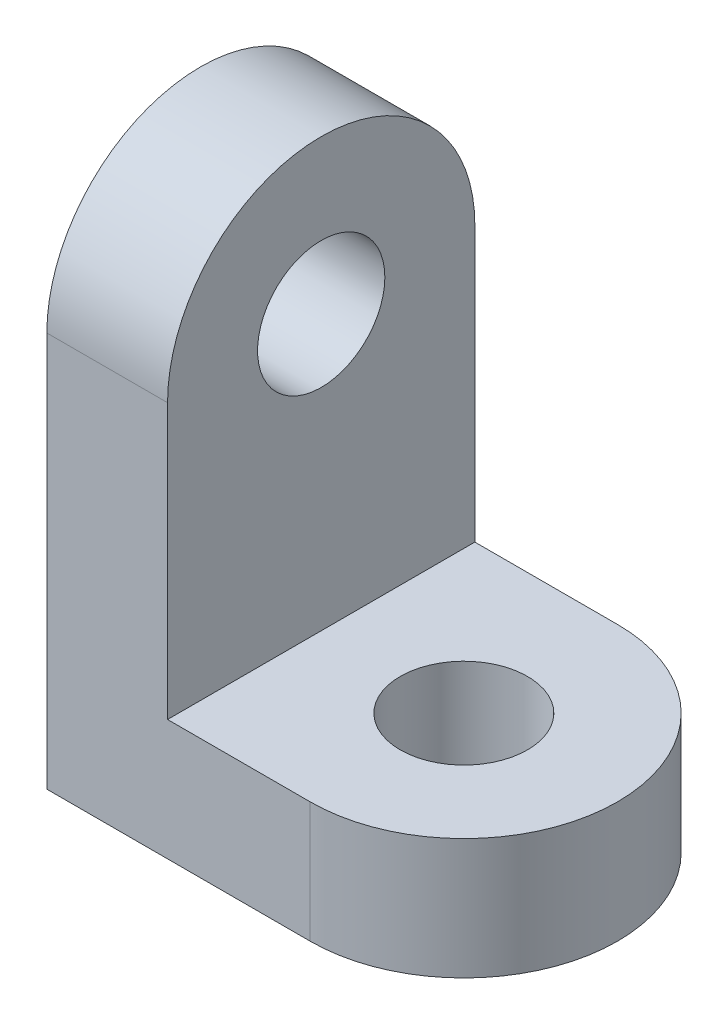
SolidWorks part; units mm, degrees
ref_plane "Front Plane" through (0, 0, 0) normal (0, 0, 1) x (1, 0, 0)
ref_plane "Top Plane" through (0, 0, 0) normal (0, 1, 0) x (1, 0, 0)
ref_plane "Right Plane" through (0, 0, 0) normal (1, 0, 0) x (0, 0, -1)
sketch "Sketch1" plane through (0, 0, 0) normal (0, 1, 0) x (1, 0, 0)
  line L1 (-3, 3.5) -> (3, 3.5)
  line L2 (-3, 3.5) -> (-3, -3.5)
  line L3 (-3, -3.5) -> (3, -3.5)
  arc A0 (3, 3.5) -> (3, -3.5) centre (3, 0) cw
  point P5 (-3, 0)
  point P6 (0, -3.5)
  dimension "D1" = 7
  dimension "D2" = 6
extrude "Boss-Extrude1" add sketch "Sketch1" along normal blind 2.75
sketch "Sketch3" plane through (0, 2.75, 0) normal (0, 1, 0) x (1, 0, 0)
  circle A0 centre (3, 0) radius 1.45
  dimension "D1" = 2.9
extrude "Cut-Extrude1" cut sketch "Sketch3" against normal blind 2.75
sketch "Sketch5" plane through (-3, 0, 0) normal (-1, 0, 0) x (0, 0, 1)
  line L1 (-3.5, 0) -> (3.5, 0)
  line L2 (-3.5, 0) -> (-3.5, 9)
  line L4 (3.5, 0) -> (3.5, 9)
  arc A0 (-3.5, 9) -> (3.5, 9) centre (0, 9) cw
  point P6 (4.4829, 7.2329)
  point P7 (0, 0)
  dimension "D1" = 9
extrude "Boss-Extrude2" add sketch "Sketch5" against normal blind 2.75
sketch "Sketch6" plane through (-0.25, 0, 0) normal (1, 0, 0) x (0, 0, -1)
  circle A0 centre (0, 9) radius 1.45
  dimension "D1" = 2.9
extrude "Cut-Extrude2" cut sketch "Sketch6" against normal blind 2.75
